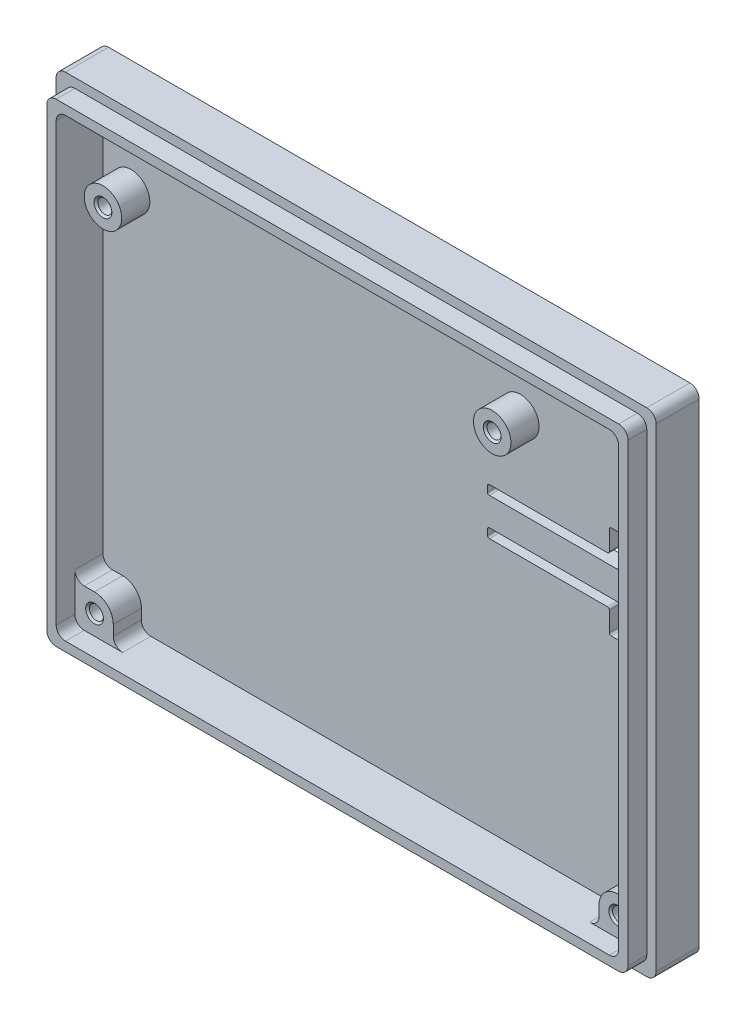
SolidWorks part; units mm, degrees
ref_plane "Front Plane" through (0, 0, 0) normal (0, 0, 1) x (1, 0, 0)
ref_plane "Top Plane" through (0, 0, 0) normal (0, 1, 0) x (1, 0, 0)
ref_plane "Right Plane" through (0, 0, 0) normal (1, 0, 0) x (0, 0, -1)
sketch "Sketch1" plane through (0, 0, 0) normal (0, 0, 1) x (1, 0, 0)
  line L0 (-2.5, 50.1) -> (61.55, 50.1)
  line L1 (0, 0) -> (59.05, 0) construction
  line L2 (0, 0) -> (0, 47.6) construction
  line L3 (0, 47.6) -> (59.05, 47.6) construction
  line L4 (59.05, 0) -> (59.05, 47.6) construction
  line L5 (61.55, -2.5) -> (61.55, 50.1)
  line L6 (-2.5, -2.5) -> (61.55, -2.5)
  line L7 (-2.5, -2.5) -> (-2.5, 50.1)
  dimension "D1" = 47.6
  dimension "D2" = 59.05
  dimension "D3" = 2.5
extrude "Boss-Extrude1" add sketch "Sketch1" along normal blind 1.6
sketch "Sketch2" plane through (0, 0, 1.6) normal (0, 0, 1) x (1, 0, 0)
  line L0 (59.55, 48.1) -> (-0.5, 48.1)
  line L1 (-0.5, 48.1) -> (-0.5, -0.5)
  line L2 (-0.5, -0.5) -> (59.55, -0.5)
  line L3 (59.55, -0.5) -> (59.55, 48.1)
  line L4 (-2.5, 50.1) -> (-2.5, -2.5)
  line L5 (-2.5, -2.5) -> (61.55, -2.5)
  line L6 (61.55, -2.5) -> (61.55, 50.1)
  line L7 (61.55, 50.1) -> (-2.5, 50.1)
  line L8 (-2.5, 50.1) -> (-2.5, -2.5)
  line L9 (-2.5, -2.5) -> (61.55, -2.5)
  line L10 (61.55, -2.5) -> (61.55, 50.1)
  line L11 (61.55, 50.1) -> (-2.5, 50.1)
  dimension "D1" = 0
  dimension "D2" = 2
extrude "Boss-Extrude2" add sketch "Sketch2" along normal blind 3
ref_plane "Plane1" through (29.525, 0, 0) normal (1, 0, 0) x (0, 0, -1)
ref_plane "Plane2" through (0, 23.8, 0) normal (0, -1, 0) x (-1, 0, 0)
sketch "Sketch6" plane through (0, 0, 4.6) normal (0, 0, 1) x (1, 0, 0)
  line L0 (60.55, -1.5) -> (60.55, 49.1)
  line L1 (-0.5, -0.5) -> (59.55, -0.5)
  line L2 (-0.5, -0.5) -> (-0.5, 48.1)
  line L3 (-0.5, 48.1) -> (59.55, 48.1)
  line L4 (59.55, -0.5) -> (59.55, 48.1)
  line L5 (-1.5, 49.1) -> (60.55, 49.1)
  line L6 (-1.5, -1.5) -> (-1.5, 49.1)
  line L7 (-1.5, -1.5) -> (60.55, -1.5)
  dimension "D1" = 1
extrude "Boss-Extrude6" add sketch "Sketch6" along normal blind 2
sketch "Sketch9" plane through (0, 0, 0) normal (0, 0, -1) x (-1, 0, 0)
  line L0 (-40.55, 27.6) -> (-54.55, 27.6)
  line L1 (-54.55, 27.6) -> (-54.55, 25.1)
  line L2 (-54.55, 25.1) -> (-57.55, 25.1)
  line L3 (-57.55, 25.1) -> (-57.55, 33.1)
  line L4 (-57.55, 33.1) -> (-54.55, 33.1)
  line L5 (-54.55, 33.1) -> (-54.55, 30.6)
  line L6 (-54.55, 30.6) -> (-40.55, 30.6)
  line L7 (-40.55, 30.6) -> (-40.55, 31.6)
  line L8 (-40.55, 31.6) -> (-53.55, 31.6)
  line L9 (-53.55, 31.6) -> (-53.55, 34.1)
  line L10 (-53.55, 34.1) -> (-58.55, 34.1)
  line L11 (-58.55, 34.1) -> (-58.55, 24.1)
  line L12 (-58.55, 24.1) -> (-53.55, 24.1)
  line L13 (-53.55, 24.1) -> (-53.55, 26.6)
  line L14 (-53.55, 26.6) -> (-40.55, 26.6)
  line L15 (-40.55, 26.6) -> (-40.55, 27.6)
  line L16 (-61.55, -2.5) -> (-61.55, 50.1) construction
  line L17 (-61.55, 50.1) -> (2.5, 50.1) construction
  point P20 (-47.55, 30.6)
  dimension "D1" = 1
  dimension "D2" = 1
  dimension "D3" = 1
  dimension "D4" = 1
  dimension "D5" = 3
  dimension "D6" = 16
  dimension "D7" = 3
  dimension "D9" = 3
  dimension "D10" = 18
  dimension "D8" = 10
  dimension "D11" = 1
extrude "Cut-Extrude2" cut sketch "Sketch9" against normal blind 2
fillet "Fillet2" radius 0.2 16 edges at (40.55, 30.6, 0.8) (40.55, 31.6, 0.8) (53.55, 34.1, 0.8) (53.55, 31.6, 0.8) (54.55, 33.1, 0.8) (54.55, 30.6, 0.8) (58.55, 34.1, 0.8) (57.55, 33.1, 0.8) (57.55, 25.1, 0.8) (58.55, 24.1, 0.8) (54.55, 25.1, 0.8) (53.55, 24.1, 0.8) (54.55, 27.6, 0.8) (40.55, 27.6, 0.8) (40.55, 26.6, 0.8) (53.55, 26.6, 0.8)
sketch "Sketch11" plane through (0, 0, 1.6) normal (0, 0, 1) x (1, 0, 0)
  line L0 (1.6, 1.6) -> (57.45, 1.6) construction
  line L1 (29.525, 48.1) -> (29.525, 1.6) construction
  line L2 (59.55, 48.1) -> (-0.5, 48.1) construction
  line L3 (2.5, 39.6) -> (44.05, 39.6) construction
  line L4 (29.525, 47.6) -> (29.525, 48.1) construction
  line L5 (0, 47.6) -> (59.05, 47.6) construction
  line L6 (0, 47.6) -> (0, 0) construction
  line L7 (0, 0) -> (59.05, 0) construction
  line L8 (59.05, 47.6) -> (59.05, 0) construction
  line L9 (59.05, 23.8) -> (59.55, 23.8) construction
  line L10 (59.55, -0.5) -> (59.55, 48.1) construction
  circle A0 centre (1.6, 1.6) radius 2
  circle A1 centre (57.45, 1.6) radius 2
  circle A2 centre (44.05, 39.6) radius 2
  circle A3 centre (2.5, 39.6) radius 2
  dimension "D1" = 55.85
  dimension "D4" = 0.9
  dimension "D7" = 1.6
  dimension "D9" = 4
  dimension "D2" = 41.55
  dimension "D3" = 38
  dimension "D5" = 59.05
  dimension "D6" = 47.6
extrude "Boss-Extrude7" add sketch "Sketch11" along normal blind 3
sketch "Sketch12" plane through (0, 0, 4.6) normal (0, 0, 1) x (1, 0, 0)
  circle A0 centre (2.5, 39.6) radius 0.75
  circle A1 centre (1.6, 1.6) radius 0.75
  circle A2 centre (57.45, 1.6) radius 0.75
  circle A3 centre (44.05, 39.6) radius 0.75
  circle A4 centre (2.5, 39.6) radius 2 construction
  circle A5 centre (1.6, 1.6) radius 2 construction
  circle A6 centre (57.45, 1.6) radius 2 construction
  circle A7 centre (44.05, 39.6) radius 2 construction
  dimension "D1" = 1.5
extrude "Cut-Extrude3" cut sketch "Sketch12" against normal blind 2
fillet "Fillet4" radius 1 10 edges at (-1.5, 49.1, 5.6) (-2.5, 50.1, 2.3) (-2.5, -2.5, 2.3) (-1.5, -1.5, 5.6) (60.55, -1.5, 5.6) (61.55, -2.5, 2.3) (60.55, 49.1, 5.6) (61.55, 50.1, 2.3) (59.55, 48.1, 4.1) (-0.5, 48.1, 4.1)
sketch "Sketch13" plane through (0, 0, 1.6) normal (0, 0, 1) x (1, 0, 0)
  line L0 (1.6, 3.6) -> (-0.5, 3.6)
  line L1 (-0.5, 47.1) -> (-0.5, -0.5) construction
  line L2 (-0.5, 3.6) -> (-0.5, -0.5)
  line L3 (-0.5, -0.5) -> (3.6, -0.5)
  line L4 (-0.5, -0.5) -> (59.55, -0.5) construction
  line L5 (3.6, -0.5) -> (3.6, 1.6)
  circle A1 centre (1.6, 1.6) radius 2 construction
  arc A3 (1.6, 3.6) -> (3.6, 1.6) centre (1.6, 1.6) ccw
extrude "Boss-Extrude8" add sketch "Sketch13" along normal up to surface (3 mm away) up to face at (2.35, 1.6, 4.6)
ref_plane "Plane3" through (29.525, 0, 0) normal (1, 0, 0) x (0, 0, -1)
mirror "Mirror1" about plane through (29.525, 0, 0) normal (1, 0, 0) of "Boss-Extrude8"
fillet "Fillet5" radius 1 6 edges at (59.55, -0.5, 5.6) (59.55, 3.6, 3.1) (55.45, -0.5, 3.1) (3.6, -0.5, 3.1) (-0.5, 3.6, 3.1) (-0.5, -0.5, 5.6)
chamfer "Chamfer2" distance 0.2 angle 45 4 edges at (3.25, 39.6, 4.6) (44.8, 39.6, 4.6) (58.2, 1.6, 4.6) (2.35, 1.6, 4.6)
equation "\"D2@Sketch9\"=\"D1@Sketch9\""
equation "\"D3@Sketch9\"=\"D1@Sketch9\""
equation "\"D4@Sketch9\"=\"D1@Sketch9\""
equation "\"D9@Sketch9\"=\"D7@Sketch9\""
